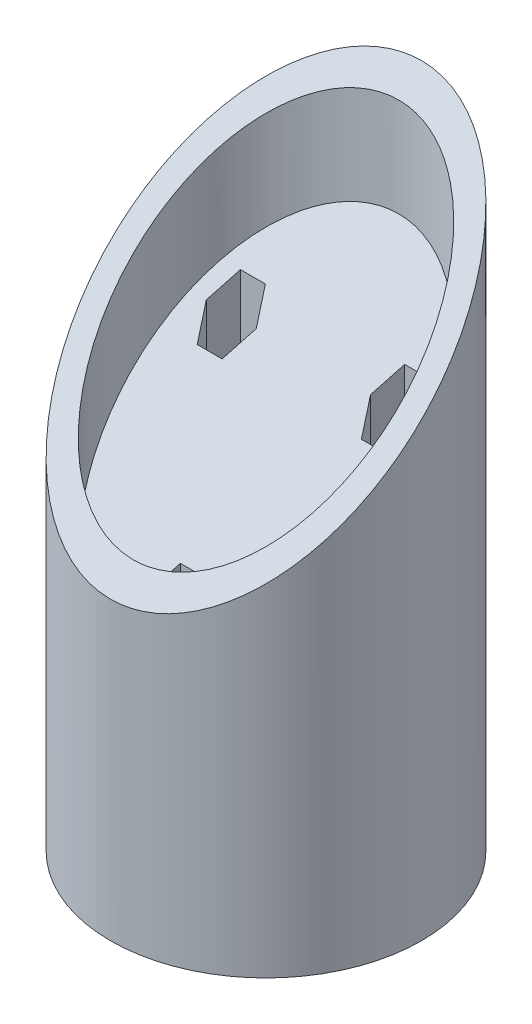
SolidWorks part; units mm, degrees
ref_plane "Спереди" through (0, 0, 0) normal (0, 0, 1) x (1, 0, 0)
ref_plane "Сверху" through (0, 0, 0) normal (0, 1, 0) x (1, 0, 0)
ref_plane "Справа" through (0, 0, 0) normal (1, 0, 0) x (0, 0, -1)
sketch "Эскиз1" plane through (0, 0, 0) normal (0, 1, 0) x (1, 0, 0)
  circle A0 centre (0, 0) radius 17.5
  circle A1 centre (0, 0) radius 20.5
  dimension "D1" = 35
  dimension "D2" = 3
extrude "Бобышка-Вытянуть1" add sketch "Эскиз1" along normal blind 59
sketch "Эскиз4" plane through (0, 59, 0) normal (0, 1, 0) x (1, 0, 0)
  line L0 (0, 0) -> (0, 20.5) construction
  circle A0 centre (0, 0) radius 20.5 construction
  point P0 (0, 20.5)
sketch "Эскиз2" plane through (0, 0, 0) normal (1, 0, 0) x (0, 0, -1)
  line L0 (-20.5, 0) -> (-20.5, 11)
  line L1 (-20.5, 0) -> (20.5, 0) construction
  line L2 (-20.5, 11) -> (20.5, 52)
  line L3 (20.5, 0) -> (20.5, 59) construction
  line L4 (-20.5, 59) -> (-20.5, 0) construction
  line L5 (20.5, 52) -> (20.5, 59)
  line L6 (20.5, 59) -> (-20.5, 59)
  line L7 (-20.5, 59) -> (-20.5, 11)
  dimension "D1" = 11
  dimension "D2" = 135
extrude "Вырез-Вытянуть1" cut sketch "Эскиз2" against normal through all and the other way through all contours L6 L7 L2 L5
sketch "Эскиз3" plane through (0, 0, 0) normal (1, 0, 0) x (0, 0, -1)
  line L0 (-17.5, 1) -> (17.5, 36)
  line L3 (17.5, 36) -> (17.5, 1)
  line L4 (17.5, 1) -> (-17.5, 1) construction
  line L5 (0, 1) -> (0, 0) construction
  line L6 (-17.5, 1) -> (-17.5, 0)
  line L7 (-17.5, 0) -> (17.5, 0)
  line L8 (17.5, 0) -> (17.5, 1)
  dimension "D1" = 35
  dimension "D2" = 45
  dimension "D3" = 1
extrude "Бобышка-Вытянуть4" add sketch "Эскиз3" along normal up to next and the other way up to next
ref_plane "Плоскость1" through (0, 59, 0) normal (0, -1, 0) x (-1, 0, 0)
sketch "Эскиз5" plane through (0, 0, 0) normal (0, -1, 0) x (1, 0, 0)
  circle A0 centre (0, 0) radius 20.5
  circle A1 centre (0, 0) radius 20.5 construction
extrude "Бобышка-Вытянуть5" add sketch "Эскиз5" along normal blind 28
sketch "Эскиз7" plane through (0, 59, 0) normal (0, -1, 0) x (-1, 0, 0)
  line L1 (-7.533, 0) -> (-3.7665, -6.5238)
  line L2 (-3.7665, -6.5238) -> (3.7665, -6.5238)
  line L3 (3.7665, -6.5238) -> (7.533, 0)
  line L4 (7.533, 0) -> (3.7665, 6.5238)
  line L5 (3.7665, 6.5238) -> (-3.7665, 6.5238)
  line L6 (-3.7665, 6.5238) -> (-7.533, 0)
  circle A0 centre (0, 0) radius 6.5238 construction
extrude "Вырез-Вытянуть2" [suppressed] cut sketch "Эскиз7" along normal blind 64
sketch "Эскиз8" [suppressed] plane through (0, -5, 0) normal (0, 1, 0) x (1, 0, 0)
  circle A0 centre (0, 0) radius 2.75
  dimension "D1" = 5.5
extrude "Вырез-Вытянуть3" [suppressed] cut sketch "Эскиз8" against normal through all
sketch "Эскиз9" plane through (0, 9.25, 9.25) normal (0, 0.7071, 0.7071) x (1, 0, 0)
  line L0 (0, 37.8302) -> (0, -11.6673) construction
  line L1 (-17.5, 13.0815) -> (17.5, 13.0815) construction
  ellipse E0 centre (0, 13.0815) end of major axis (0, -11.6673) minor radius 17.5 construction
  point P13 (0, 13.0815)
sketch "Эскиз10" plane through (0, 15.75, 15.75) normal (0, 0.7071, 0.7071) x (1, 0, 0)
  line L0 (0, 47.0226) -> (0, -2.4749) construction
  line L1 (17.5, 22.2739) -> (-17.5, 22.2739) construction
  ellipse E0 centre (0, 22.2739) end of major axis (0, 47.0226) minor radius 17.5 construction
  point P13 (0, 22.2739)
sketch "Эскиз11" plane through (0, -28, 0) normal (0, -1, 0) x (1, 0, 0)
  line L0 (0, 0) -> (0, 12.5) construction
  line L1 (0, 0) -> (10.8253, -6.25) construction
  line L2 (0, 0) -> (-10.8253, -6.25) construction
  circle A0 centre (0, 0) radius 12.5 construction
  point P6 (11.0835, -6.6973)
  point P7 (-11.2149, -6.4749)
  dimension "D3" = 25
  dimension "D1" = 120
  dimension "D2" = 120
sketch "Эскиз13" plane through (0, 59, 0) normal (0, -1, 0) x (-1, 0, 0)
  line L1 (7.5344, 6.25) -> (9.1799, 3.4)
  line L2 (9.1799, 3.4) -> (12.4708, 3.4)
  line L3 (12.4708, 3.4) -> (14.1162, 6.25)
  line L4 (14.1162, 6.25) -> (12.4708, 9.1)
  line L5 (12.4708, 9.1) -> (9.1799, 9.1)
  line L6 (9.1799, 9.1) -> (7.5344, 6.25)
  line L7 (-14.1162, 6.25) -> (-12.4708, 3.4)
  line L8 (-12.4708, 3.4) -> (-9.1799, 3.4)
  line L9 (-9.1799, 3.4) -> (-7.5344, 6.25)
  line L10 (-7.5344, 6.25) -> (-9.1799, 9.1)
  line L11 (-9.1799, 9.1) -> (-12.4708, 9.1)
  line L12 (-12.4708, 9.1) -> (-14.1162, 6.25)
  line L13 (-3.2909, -12.5) -> (-1.6454, -15.35)
  line L14 (-1.6454, -15.35) -> (1.6454, -15.35)
  line L15 (1.6454, -15.35) -> (3.2909, -12.5)
  line L16 (3.2909, -12.5) -> (1.6454, -9.65)
  line L17 (1.6454, -9.65) -> (-1.6454, -9.65)
  line L18 (-1.6454, -9.65) -> (-3.2909, -12.5)
  circle A0 centre (10.8253, 6.25) radius 2.85 construction
  circle A1 centre (-10.8253, 6.25) radius 2.85 construction
  circle A2 centre (0, -12.5) radius 2.85 construction
  dimension "D1" = 5.7
  dimension "D2" = 5.7
  dimension "D3" = 5.7
extrude "Вырез-Вытянуть6" cut sketch "Эскиз13" along normal blind 84
sketch "Эскиз15" plane through (0, -25, 0) normal (0, 1, 0) x (1, 0, 0)
  circle A0 centre (10.8253, 6.25) radius 1.75
  circle A1 centre (-10.8253, 6.25) radius 1.75
  circle A2 centre (0, -12.5) radius 1.75
  dimension "D1" = 3.5
  dimension "D2" = 3.5
  dimension "D3" = 3.5
extrude "Вырез-Вытянуть7" cut sketch "Эскиз15" against normal through all
